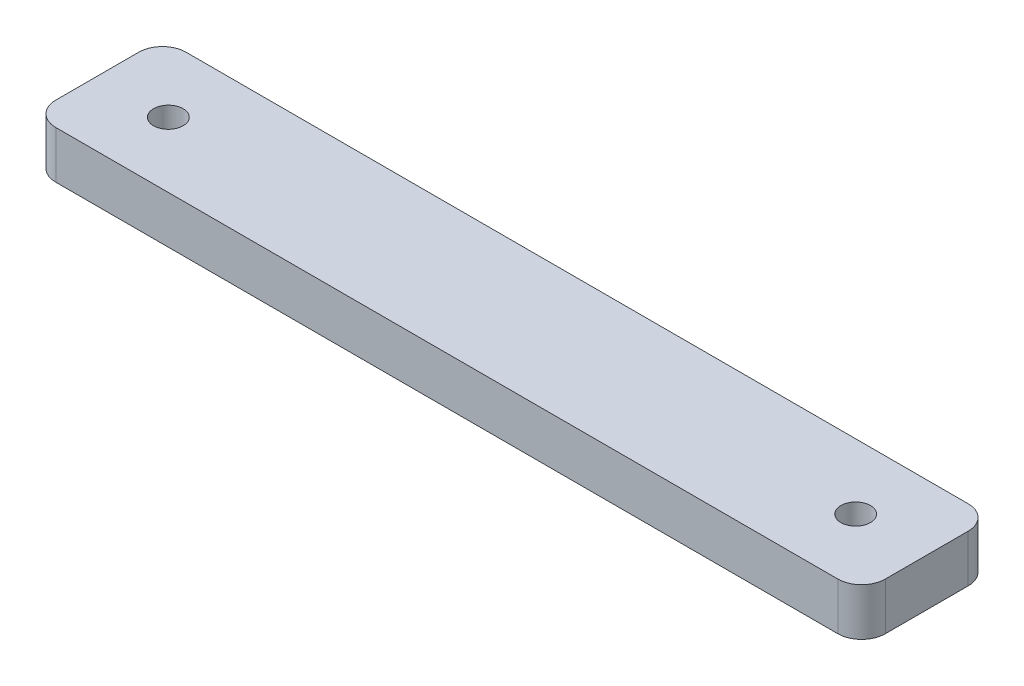
SolidWorks part; units mm, degrees
ref_plane "Front" through (0, 0, 0) normal (0, 0, 1) x (1, 0, 0)
ref_plane "Top" through (0, 0, 0) normal (0, 1, 0) x (1, 0, 0)
ref_plane "Right" through (0, 0, 0) normal (1, 0, 0) x (0, 0, -1)
sketch "Croquis1" plane through (0, 0, 0) normal (0, 1, 0) x (1, 0, 0)
  line L0 (-72.6012, 0) -> (3557.4579, 0) construction
  line L1 (0, -72.6012) -> (0, 3557.4579) construction
  line L3 (-17.5, -2.75) -> (17.5, -2.75)
  line L4 (-17.5, -2.75) -> (-17.5, 2.75)
  line L5 (-17.5, 2.75) -> (17.5, 2.75)
  line L6 (17.5, -2.75) -> (17.5, 2.75)
  line L7 (-17.5, -2.75) -> (17.5, 2.75) construction
  line L8 (-17.5, 2.75) -> (17.5, -2.75) construction
  circle A0 centre (-14.5, 0) radius 0.625
  circle A1 centre (14.5, 0) radius 0.625
  point P4 (0, 0)
  dimension "D3" = 1.25
  dimension "D4" = 3
  dimension "D1" = 5.5
  dimension "D2" = 35
extrude "Saliente-Extruir1" add sketch "Croquis1" along normal blind 2
fillet "Redondeo1" radius 1 4 edges at (17.5, 1, 2.75) (17.5, 1, -2.75) (-17.5, 1, -2.75) (-17.5, 1, 2.75)
